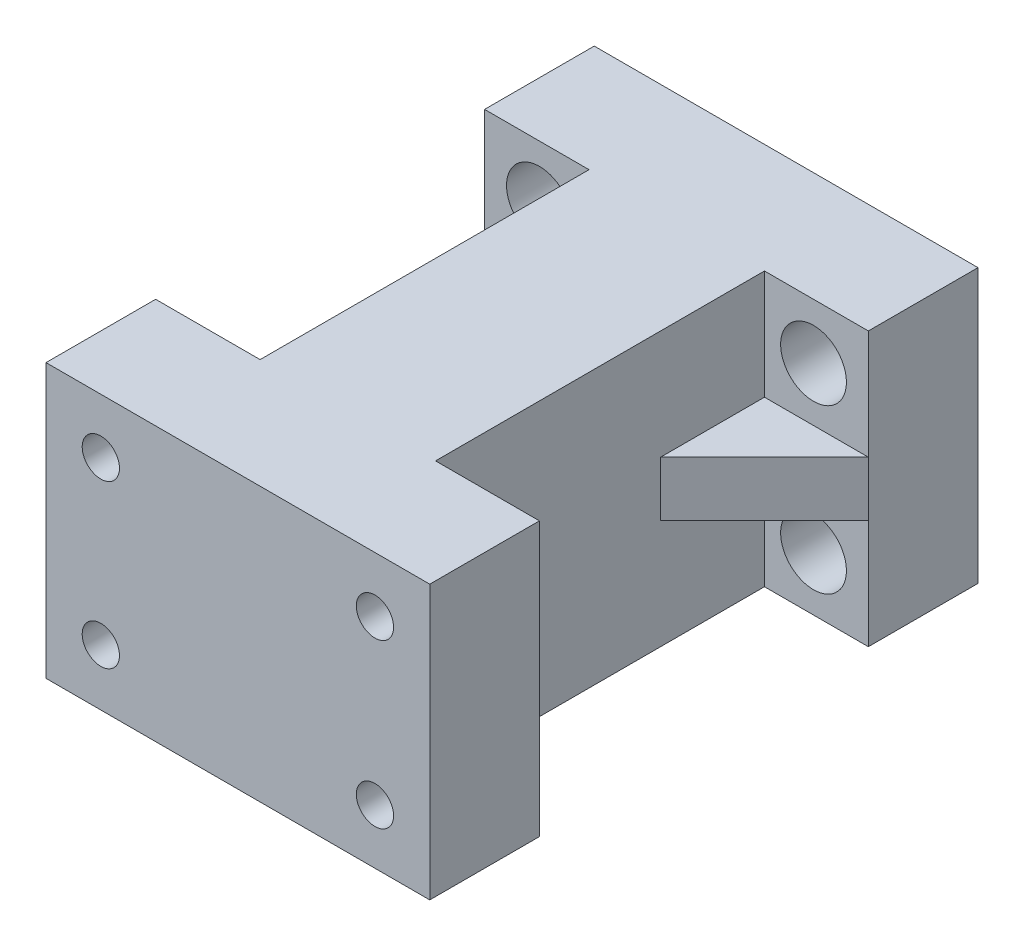
SolidWorks part; units mm, degrees
material "Custom Plastic"
ref_plane "Front Plane" through (0, 0, 0) normal (0, 0, 1) x (1, 0, 0)
ref_plane "Top Plane" through (0, 0, 0) normal (0, 1, 0) x (1, 0, 0)
ref_plane "Right Plane" through (0, 0, 0) normal (1, 0, 0) x (0, 0, -1)
sketch "Sketch2" plane through (0, 0, 0) normal (0, 0, 1) x (1, 0, 0)
  line L0 (-5.7762, -68.8764) -> (-5.7762, -53.8764)
  line L1 (-5.7762, -68.8764) -> (-5.7762, -53.8764) construction
  line L2 (29.2238, -68.8764) -> (29.2238, -53.8764)
  line L3 (29.2238, -68.8764) -> (29.2238, -53.8764) construction
  line L4 (29.2238, -53.8764) -> (29.2238, 49946.1236) construction
  line L5 (-5.7762, -53.8764) -> (-5.7762, 49946.1236) construction
  line L6 (264.0238, 235.9236) -> (-40.7762, 235.9236) construction
  line L7 (264.0238, 235.9236) -> (-40.7762, 235.9236)
  line L9 (29.2238, 235.9236) -> (-5.7762, 235.9236)
  line L10 (29.2238, 235.9236) -> (29.2238, 210.9822)
  line L11 (29.2238, 210.9822) -> (-5.7762, 210.9822)
  line L12 (-5.7762, 235.9236) -> (-5.7762, 210.9822)
  line L13 (-5.7762, 235.9236) -> (-0.7762, 235.9236)
  line L15 (-5.7762, 235.9236) -> (-5.7762, 230.9236)
  line L16 (-5.7762, 230.9236) -> (-0.7762, 230.9236) construction
  line L17 (-0.7762, 235.9236) -> (-0.7762, 230.9236) construction
  line L18 (29.2238, 235.9236) -> (24.2238, 235.9236)
  line L19 (29.2238, 235.9236) -> (29.2238, 230.865)
  line L20 (29.2238, 230.865) -> (24.2238, 230.865) construction
  line L21 (24.2238, 235.9236) -> (24.2238, 230.865) construction
  line L22 (29.2238, 210.9822) -> (24.2238, 210.9822)
  line L23 (29.2238, 210.9822) -> (29.2238, 215.9822)
  line L24 (29.2238, 215.9822) -> (24.2238, 215.9822) construction
  line L25 (24.2238, 210.9822) -> (24.2238, 215.9822) construction
  line L26 (-5.7762, 210.9822) -> (-0.7762, 210.9822) construction
  line L27 (-5.7762, 210.9822) -> (-5.7762, 216.1306) construction
  line L28 (-5.7762, 216.1306) -> (-0.7762, 216.1306) construction
  line L29 (-0.7762, 210.9822) -> (-0.7762, 216.1306) construction
  circle A0 centre (24.4871, -61.3764) radius 3 construction
  circle A1 centre (-1.0129, -61.3764) radius 3 construction
  circle A2 centre (24.4871, -61.3764) radius 3 construction
  circle A3 centre (-1.0129, -61.3764) radius 3 construction
  circle A7 centre (-0.7762, 230.9236) radius 1.7
  circle A8 centre (24.2238, 230.865) radius 1.7
  circle A9 centre (-0.7762, 216.1306) radius 1.7
  circle A10 centre (24.2238, 215.9822) radius 1.7
extrude "Boss-Extrude1" add sketch "Sketch2" along normal blind 50
sketch "Sketch3" plane through (0, 235.9236, 0) normal (0, 1, 0) x (1, 0, 0)
  line L2 (19.7505, -10) -> (29.2238, -10)
  line L3 (3.7505, -40) -> (-5.7762, -40)
  line L4 (-5.7762, 0) -> (-5.7762, -50)
  line L5 (-5.7762, -50) -> (29.2238, -50)
  line L6 (29.2238, -50) -> (29.2238, 0)
  line L7 (19.7505, -27) -> (19.7505, -10)
  line L8 (19.7505, -10) -> (29.2238, -10)
  line L9 (29.2238, -10) -> (29.2238, 0)
  line L10 (29.2238, 0) -> (-5.7762, 0)
  line L11 (-5.7762, 0) -> (-5.7762, -10)
  line L12 (-5.7762, -10) -> (3.7505, -10)
  line L13 (3.7505, -10) -> (3.7505, -27)
  line L14 (19.7505, -27) -> (19.7505, -10)
  line L15 (19.7505, -10) -> (29.2238, -10)
  line L16 (29.2238, -10) -> (29.2238, 0)
  line L17 (29.2238, 0) -> (-5.7762, 0)
  line L18 (-5.7762, 0) -> (-5.7762, -10)
  line L19 (-5.7762, -10) -> (3.7505, -10)
  line L20 (3.7505, -10) -> (3.7505, -27)
  line L21 (29.2238, 0) -> (-5.7762, 0)
  line L22 (-5.7762, 0) -> (-5.7762, -50)
  line L23 (-5.7762, -50) -> (29.2238, -50)
  line L24 (29.2238, -50) -> (29.2238, 0)
  line L25 (29.2238, 0) -> (-5.7762, 0)
  line L27 (3.7505, -50) -> (-5.7762, -50)
  line L28 (-5.7762, -40) -> (-5.7762, -50)
  line L29 (3.7505, -40) -> (-5.7762, -40)
  line L30 (3.7505, -40) -> (3.7505, -10)
  line L31 (3.7505, -10) -> (-5.7762, -10)
  line L32 (-5.7762, -40) -> (-5.7762, -10)
  line L33 (19.7505, -10) -> (19.7505, -40)
  line L34 (19.7505, -40) -> (29.2238, -40)
  line L35 (29.2238, -10) -> (29.2238, -40)
  circle A1 centre (11.7431, -25.37) radius 4
  circle A2 centre (11.7431, -25.37) radius 4
  arc A4 (3.7505, -27) -> (11.7505, -35) centre (11.7505, -27) ccw
  arc A5 (11.7505, -35) -> (19.7505, -27) centre (11.7505, -27) ccw
  dimension "D4" = 10
  dimension "D5" = 10
  dimension "D1" = 0
  dimension "D2" = 0
  dimension "D3" = 0
extrude "Cut-Extrude1" cut sketch "Sketch3" against normal blind 51
sketch "Sketch4" plane through (0, 210.9822, 0) normal (0, -1, 0) x (1, 0, 0)
  circle A0 centre (11.7431, 25.37) radius 4.1 construction
  circle A1 centre (11.7431, 25.37) radius 4.1
extrude "Cut-Extrude2" cut sketch "Sketch4" against normal up to surface (22.1816 mm away)
sketch "Sketch6" plane through (0, 0, 10) normal (0, 0, 1) x (1, 0, 0)
  circle A1 centre (24.2238, 230.865) radius 3
  circle A2 centre (-0.7762, 230.9236) radius 1.7 construction
  circle A3 centre (-0.7762, 230.9236) radius 1.7
  circle A4 centre (-0.7762, 216.1306) radius 1.7 construction
  circle A5 centre (24.2238, 215.9822) radius 1.7 construction
  circle A6 centre (-0.7762, 216.1306) radius 1.7
  circle A7 centre (24.2238, 215.9822) radius 1.7
  circle A8 centre (24.2238, 215.9822) radius 3
  circle A9 centre (-0.7762, 216.1306) radius 3
  circle A10 centre (-0.7762, 230.9236) radius 3
extrude "Cut-Extrude3" cut sketch "Sketch6" against normal blind 6
ref_plane "Plane1" through (0, 223.4529, 0) normal (0, 1, 0) x (1, 0, 0)
sketch "Sketch8" plane through (0, 223.4529, 0) normal (0, 1, 0) x (1, 0, 0)
  line L0 (29.2238, -40) -> (19.7505, -30.5267)
  line L1 (29.2238, -10) -> (19.7505, -19.4733)
  line L2 (-5.7762, -10) -> (3.7505, -19.5267)
  line L3 (-5.6517, -40) -> (3.7505, -30.5978)
  line L5 (-5.7762, -50) -> (-5.7762, -40) construction
  line L6 (-5.7762, -50) -> (-5.7762, -40)
  line L12 (-5.7762, -40) -> (-5.7762, -50)
  line L13 (3.7505, -40) -> (-5.7762, -40)
  line L14 (3.7505, -10) -> (3.7505, -40)
  line L15 (-5.7762, -10) -> (3.7505, -10)
  line L16 (-5.7762, 0) -> (-5.7762, -10)
  line L17 (29.2238, 0) -> (-5.7762, 0)
  line L18 (29.2238, -10) -> (29.2238, 0)
  line L19 (19.7505, -10) -> (29.2238, -10)
  line L20 (19.7505, -40) -> (19.7505, -10)
  line L21 (29.2238, -40) -> (19.7505, -40)
  line L22 (29.2238, -50) -> (29.2238, -40)
  line L23 (-5.7762, -50) -> (29.2238, -50)
  line L25 (-5.6517, -40) -> (-5.7762, -40)
  line L26 (3.7505, -19.5267) -> (3.7505, -30.5978)
  line L28 (-5.7762, 0) -> (-5.7762, -10)
  line L29 (29.2238, 0) -> (-5.7762, 0)
  line L30 (29.2238, -10) -> (29.2238, 0)
  line L32 (19.7505, -30.5267) -> (19.7505, -19.4733)
  line L34 (29.2238, -50) -> (29.2238, -40)
  line L35 (-5.7762, -50) -> (29.2238, -50)
  line L43 (3.7505, -40) -> (-5.7762, -40)
  line L44 (-5.7762, -40) -> (-5.7762, -50)
  line L45 (-5.7762, -50) -> (29.2238, -50)
  line L46 (29.2238, -50) -> (29.2238, -40)
  line L47 (29.2238, -40) -> (19.7505, -40)
  line L48 (19.7505, -40) -> (19.7505, -10)
  line L49 (19.7505, -10) -> (29.2238, -10)
  line L50 (29.2238, -10) -> (29.2238, 0)
  line L51 (29.2238, 0) -> (-5.7762, 0)
  line L52 (-5.7762, 0) -> (-5.7762, -10)
  line L53 (-5.7762, -10) -> (3.7505, -10)
  line L54 (3.7505, -10) -> (3.7505, -40)
  line L55 (3.7505, -40) -> (-5.7762, -40)
  line L56 (-5.7762, -40) -> (-5.7762, -50)
  line L57 (-5.7762, -50) -> (29.2238, -50)
  line L58 (29.2238, -50) -> (29.2238, -40)
  line L59 (29.2238, -40) -> (19.7505, -40)
  line L60 (19.7505, -40) -> (19.7505, -10)
  line L61 (19.7505, -10) -> (29.2238, -10)
  line L62 (29.2238, -10) -> (29.2238, 0)
  line L63 (29.2238, 0) -> (-5.7762, 0)
  line L64 (-5.7762, 0) -> (-5.7762, -10)
  line L65 (-5.7762, -10) -> (3.7505, -10)
  line L66 (3.7505, -10) -> (3.7505, -40)
  dimension "D2" = 0
  dimension "D1" = 0
extrude "Boss-Extrude2" add sketch "Sketch8" along normal mid plane 5 contours L66 L3 L55 | L60 L59 L0 | L61 L60 L1 | L66 L65 L2
